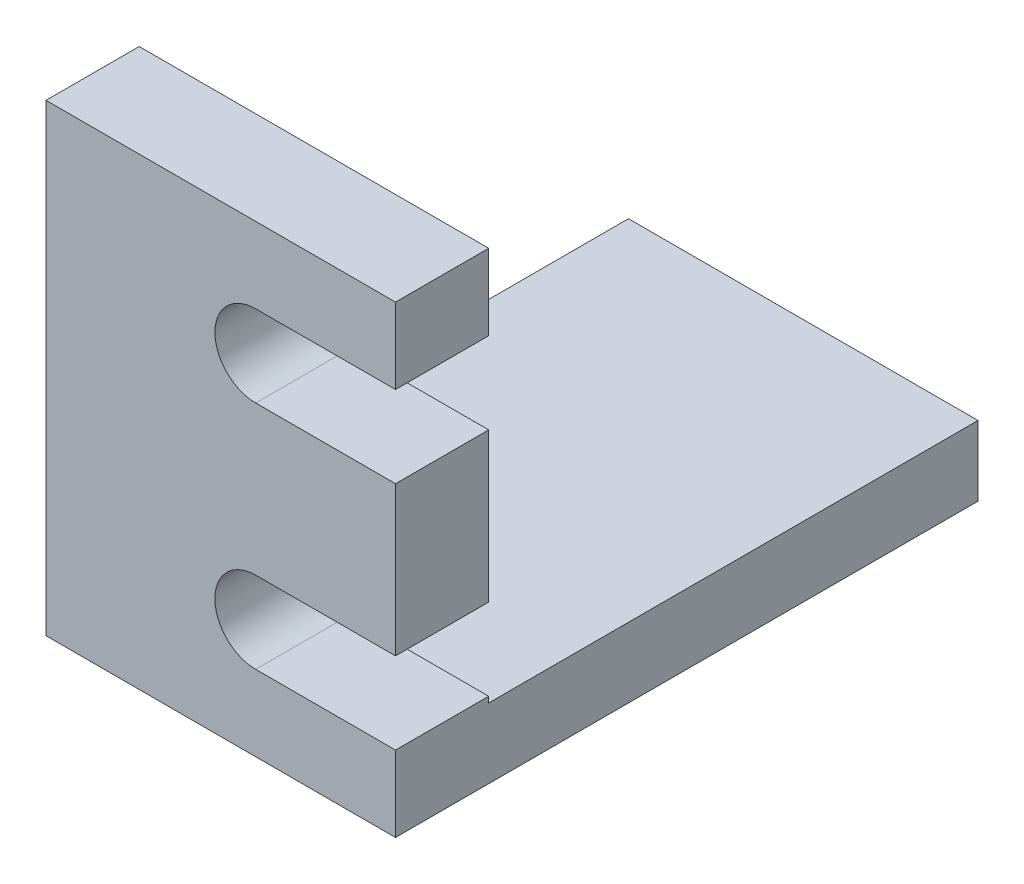
SolidWorks part; units mm, degrees
ref_plane "Piano frontale" through (0, 0, 0) normal (0, 0, 1) x (1, 0, 0)
ref_plane "Piano superiore" through (0, 0, 0) normal (0, 1, 0) x (1, 0, 0)
ref_plane "Piano destro" through (0, 0, 0) normal (1, 0, 0) x (0, 0, -1)
sketch "Schizzo1" plane through (0, 0, 0) normal (0, 0, 1) x (1, 0, 0)
  line L0 (0, 0) -> (0, 19.9)
  line L1 (0, 0) -> (15, 0)
  line L2 (0, 19.9) -> (15, 19.9)
  line L3 (15, 0) -> (15, 19.9)
  line L4 (15, 9.95) -> (12, 9.95) construction
  line L5 (12, 9.95) -> (12, 14.9) construction
  line L6 (12, 9.95) -> (12, 5) construction
  line L7 (9, 5) -> (15, 5) construction
  line L8 (9, 6.75) -> (15, 6.75)
  line L9 (9, 3.25) -> (15, 3.25)
  line L10 (9, 6.75) -> (9, 3.25) construction
  line L11 (9, 14.9) -> (15, 14.9) construction
  line L12 (9, 16.65) -> (15, 16.65)
  line L13 (9, 13.15) -> (15, 13.15)
  line L14 (9, 16.65) -> (9, 13.15) construction
  arc A0 (9, 6.75) -> (9, 3.25) centre (9, 5) ccw
  arc A1 (15, 3.25) -> (15, 6.75) centre (15, 5) ccw
  arc A2 (9, 16.65) -> (9, 13.15) centre (9, 14.9) ccw
  arc A3 (15, 13.15) -> (15, 16.65) centre (15, 14.9) ccw
  point P11 (12, 5)
  point P20 (12, 14.9)
extrude "Estrusione-Estrusione1" add sketch "Schizzo1" along normal blind 4 contours A2 L12 L3 L2 L0 L1 L9 A0 L8 L13
sketch "Schizzo2" plane through (0, 0, 0) normal (0, 0, -1) x (-1, 0, 0)
  line L0 (-15, 0) -> (0, 0)
  line L1 (-15, 0) -> (-15, 3)
  line L2 (0, 0) -> (0, 3)
  line L3 (-15, 3) -> (0, 3)
extrude "Estrusione-Estrusione2" add sketch "Schizzo2" along normal blind 21
